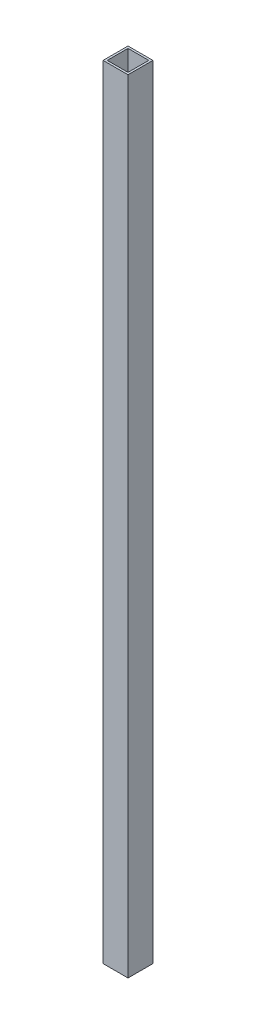
SolidWorks part; units mm, degrees
ref_plane "Front Plane" through (0, 0, 0) normal (0, 0, 1) x (1, 0, 0)
ref_plane "Top Plane" through (0, 0, 0) normal (0, 1, 0) x (1, 0, 0)
ref_plane "Right Plane" through (0, 0, 0) normal (1, 0, 0) x (0, 0, -1)
sketch "Sketch1" plane through (0, 0, 0) normal (0, 1, 0) x (1, 0, 0)
  line L0 (-2.025, 2.025) -> (2.025, 2.025)
  line L1 (-2.425, 2.425) -> (2.425, 2.425)
  line L2 (-2.425, 2.425) -> (-2.425, -2.425)
  line L3 (-2.425, -2.425) -> (2.425, -2.425)
  line L4 (2.425, 2.425) -> (2.425, -2.425)
  line L5 (-2.425, 2.425) -> (2.425, -2.425) construction
  line L6 (-2.425, -2.425) -> (2.425, 2.425) construction
  line L7 (2.025, 2.025) -> (2.025, -2.025)
  line L8 (-2.025, -2.025) -> (2.025, -2.025)
  line L9 (-2.025, 2.025) -> (-2.025, -2.025)
  point P0 (0, 0)
  dimension "D1" = 4.85
  dimension "D2" = 0.4
extrude "Boss-Extrude1" add sketch "Sketch1" along normal blind 152.4
sketch "Sketch2" plane through (0, 152.4, 0) normal (0, 1, 0) x (1, 0, 0)
  line L1 (-2.425, 2.425) -> (2.425, 2.425)
  line L2 (-2.425, 2.425) -> (-2.425, -2.425)
  line L3 (-2.425, -2.425) -> (2.425, -2.425)
  line L4 (2.425, 2.425) -> (2.425, -2.425)
  line L5 (-2.425, 2.425) -> (2.425, -2.425) construction
  line L6 (-2.425, -2.425) -> (2.425, 2.425) construction
  point P0 (0, 0)
sketch "Sketch5" plane through (0, 0, 0) normal (0, -1, 0) x (1, 0, 0)
  line L0 (-2.425, -2.425) -> (-2.425, 2.425) construction
  circle A0 centre (0, 0) radius 2.425 construction
sketch "Sketch7" plane through (2.425, 0, 0) normal (1, 0, 0) x (0, 0, -1)
  line L0 (0, 152.4) -> (0, 0) construction
  line L1 (-2.425, 152.4) -> (2.425, 152.4) construction
  line L2 (-2.425, 0) -> (2.425, 0) construction
